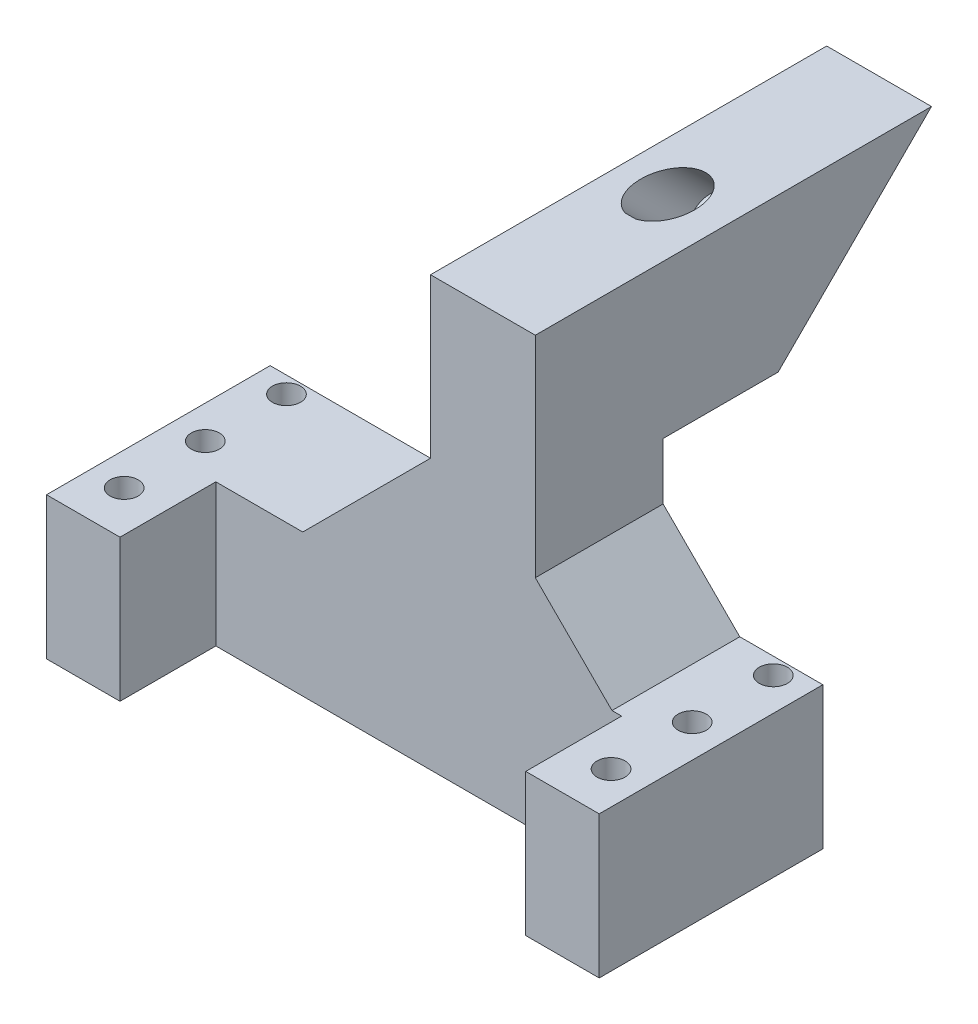
SolidWorks part; units mm, degrees
ref_plane "Front Plane" through (0, 0, 0) normal (0, 0, 1) x (1, 0, 0)
ref_plane "Top Plane" through (0, 0, 0) normal (0, 1, 0) x (1, 0, 0)
ref_plane "Right Plane" through (0, 0, 0) normal (1, 0, 0) x (0, 0, -1)
sketch "Sketch1" plane through (0, 0, 0) normal (1, 0, 0) x (0, 0, -1)
  line L1 (-17.5, -11.125) -> (17.5, -11.125)
  line L2 (-17.5, -11.125) -> (-17.5, 11.125)
  line L3 (-17.5, 11.125) -> (17.5, 11.125)
  line L4 (17.5, -11.125) -> (17.5, 11.125)
  line L5 (-17.5, -11.125) -> (17.5, 11.125) construction
  line L6 (-17.5, 11.125) -> (17.5, -11.125) construction
  point P0 (0, 0)
extrude "Boss-Extrude1" add sketch "Sketch1" along normal blind 11.5
sketch "Sketch2" plane through (0, 11.125, 0) normal (0, 1, 0) x (1, 0, 0)
  line L0 (11.5, -17.5) -> (0, -17.5) construction
  line L5 (11.5, 17.5) -> (11.5, -17.5) construction
  circle A0 centre (5.15, -10.5) radius 2.2
  dimension "D1" = 6.35
  dimension "D2" = 7
extrude "Cut-Extrude1" cut sketch "Sketch2" against normal through all
pattern_linear "LPattern1" count 3 spacing 12.7 along (0, 0, -1) of "Cut-Extrude1"
ref_plane "Plane1" through (43.25, 0, 0) normal (1, 0, 0) x (0, 0, -1)
mirror "Mirror3" about plane through (43.25, 0, 0) normal (1, 0, 0) of bodies 103
sketch "Sketch3" plane through (11.5, 0, 0) normal (1, 0, 0) x (0, 0, -1)
  line L0 (-2.5, 11.125) -> (-2.5, -11.125)
  line L1 (17.5, 11.125) -> (-17.5, 11.125) construction
  line L2 (-17.5, -11.125) -> (17.5, -11.125) construction
  line L3 (-2.5, -11.125) -> (17.5, -11.125)
  line L4 (17.5, -11.125) -> (17.5, 11.125)
  line L5 (17.5, 11.125) -> (-2.5, 11.125)
extrude "Boss-Extrude2" add sketch "Sketch3" along normal blind 50
sketch "Sketch4" plane through (0, 11.125, 0) normal (0, 1, 0) x (1, 0, 0)
  line L0 (53.3, 17.5) -> (53.3, -2.5) construction
  line L1 (61.5, 17.5) -> (0, 17.5) construction
  line L2 (61.5, -2.5) -> (11.5, -2.5) construction
  line L3 (11.5, -2.5) -> (11.5, -17.5) construction
  line L5 (45.1, -2.5) -> (61.5, -2.5)
  line L6 (45.1, -2.5) -> (45.1, 17.5)
  line L7 (45.1, 17.5) -> (61.5, 17.5)
  line L8 (61.5, -2.5) -> (61.5, 17.5)
  line L9 (45.1, -2.5) -> (61.5, 17.5) construction
  line L10 (45.1, 17.5) -> (61.5, -2.5) construction
  point P8 (53.3, 7.5)
  dimension "D1" = 41.8
extrude "Boss-Extrude3" add sketch "Sketch4" along normal blind 44.87
chamfer "Chamfer1" distance 20 angle 45 1 edges at (45.1, 11.125, -7.5)
sketch "Sketch5" plane through (61.5, 0, 0) normal (1, 0, 0) x (0, 0, -1)
  line L0 (-2.5, 55.995) -> (-2.5, -11.125) construction
  line L1 (17.5, -11.125) -> (-2.5, -11.125)
  line L2 (17.5, -11.125) -> (17.5, 11.125)
  line L3 (17.5, 11.125) -> (-2.5, 11.125)
  line L4 (-2.5, -11.125) -> (-2.5, 11.125)
extrude "Boss-Extrude4" add sketch "Sketch5" along normal blind 15
chamfer "Chamfer2" distance 12 angle 45 1 edges at (61.5, 11.125, -7.5)
sketch "Sketch6" plane through (0, 0, -17.5) normal (0, 0, -1) x (-1, 0, 0)
  line L0 (-45.1, 55.995) -> (-45.1, 31.125) construction
  line L1 (-61.5, 55.995) -> (-45.1, 55.995)
  line L2 (-61.5, 55.995) -> (-61.5, 31.995)
  line L3 (-61.5, 31.995) -> (-45.1, 31.995)
  line L4 (-45.1, 55.995) -> (-45.1, 31.995)
extrude "Boss-Extrude5" add sketch "Sketch6" along normal blind 18
sketch "Sketch7" plane through (61.5, 0, 0) normal (1, 0, 0) x (0, 0, -1)
  line L0 (35.5, 31.995) -> (59.5, 55.995)
  line L1 (59.5, 55.995) -> (35.5, 55.995)
  line L2 (35.5, 55.995) -> (35.5, 31.995)
  dimension "D1" = 45
extrude "Boss-Extrude6" add sketch "Sketch7" against normal blind 16.4
sketch "Sketch11" plane through (0, -1.7525, -1.7525) normal (0, -0.7071, -0.7071) x (1, 0, 0)
  circle A0 centre (52.7781, -58.6439) radius 2.35
extrude "Cut-Extrude4" cut sketch "Sketch11" against normal through all
sketch3d "3DSketch2"
  line L0 (52.7781, 39.715, -43.22) -> (52.7781, 58.9172, -24.0178) construction
  line L1 (52.7781, 57.6567, -25.2783) -> (52.7781, 39.715, -43.22) construction
  line L2 (52.7781, 58.9172, -24.0178) -> (41.1389, 58.9172, -24.0178) construction
  line L3 (52.7781, 58.9172, -24.0178) -> (52.7781, 64.5519, -29.6525) construction
ref_plane "Plane4" through (0, 17.4497, 17.4497) normal (0, 0.7071, 0.7071) x (1, 0, 0)
sketch "Sketch12" plane through (0, 17.4497, 17.4497) normal (0, 0.7071, 0.7071) x (1, 0, 0)
  circle A0 centre (52.7781, 58.6439) radius 4.2
extrude "Cut-Extrude5" cut sketch "Sketch12" against normal blind 16
